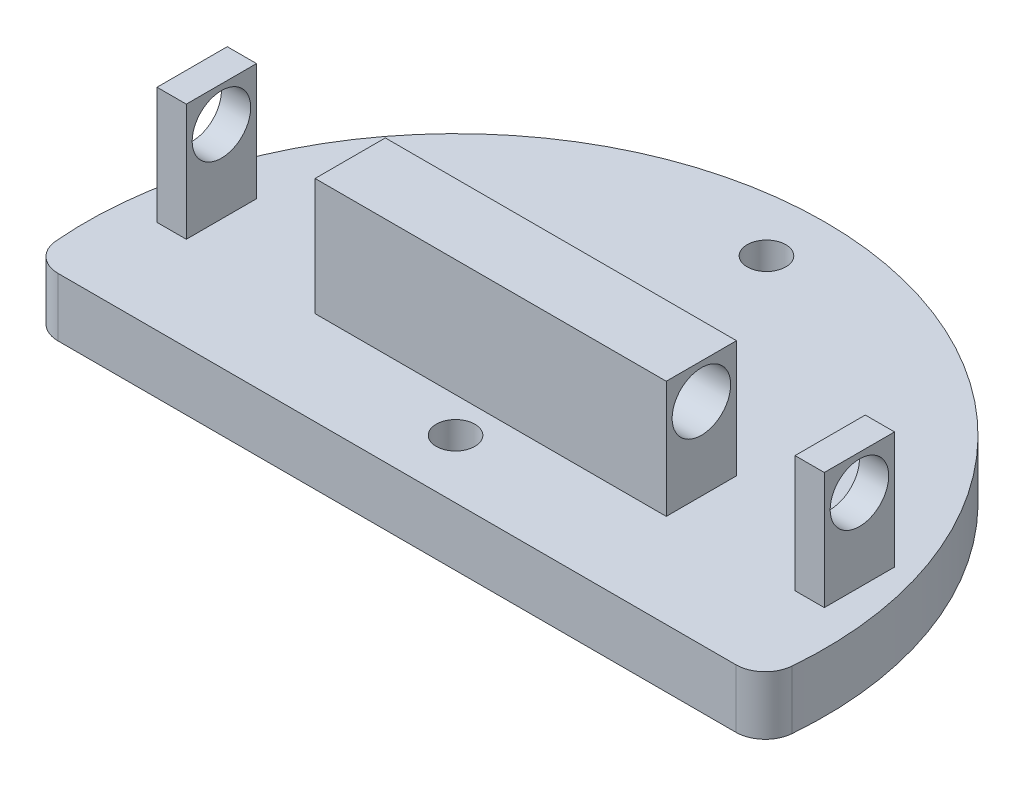
SolidWorks part; units mm, degrees
ref_plane "Front Plane" through (0, 0, 0) normal (0, 0, 1) x (1, 0, 0)
ref_plane "Top Plane" through (0, 0, 0) normal (0, 1, 0) x (1, 0, 0)
ref_plane "Right Plane" through (0, 0, 0) normal (1, 0, 0) x (0, 0, -1)
sketch "Sketch1" plane through (0, 0, 0) normal (0, 1, 0) x (1, 0, 0)
  line L0 (0, 0) -> (0, -5)
  line L1 (0, 26.56) -> (0, 31.56)
  line L2 (0, -5) -> (-31.1614, -5)
  line L3 (0, -5) -> (31.1614, -5)
  circle A0 centre (0, 0) radius 1.65
  circle A1 centre (0, 26.56) radius 1.65
  arc A3 (-31.1614, -5) -> (31.1614, -5) centre (0, 0) cw
  dimension "D1" = 3.3
  dimension "D2" = 3.3
  dimension "D3" = 26.56
  dimension "D5" = 5
  dimension "D4" = 5
extrude "Boss-Extrude1" add sketch "Sketch1" along normal blind 5
fillet "Fillet1" radius 2.5 2 edges at (-31.1614, 2.5, 5) (31.1614, 2.5, 5)
sketch "Sketch2" plane through (0, 5, 0) normal (0, 1, 0) x (1, 0, 0)
  line L0 (0, 0) -> (0, 3) construction
  line L2 (-28.5, 3) -> (-26, 3)
  line L3 (-28.5, 3) -> (-28.5, 9)
  line L4 (-28.5, 9) -> (-26, 9)
  line L5 (-26, 3) -> (-26, 9)
  line L6 (26, 3) -> (28.5, 3)
  line L7 (26, 3) -> (26, 9)
  line L8 (26, 9) -> (28.5, 9)
  line L9 (28.5, 3) -> (28.5, 9)
  line L10 (-15, 3) -> (15, 3)
  line L11 (-15, 3) -> (-15, 9)
  line L12 (-15, 9) -> (15, 9)
  line L13 (15, 3) -> (15, 9)
  dimension "D1" = 3
  dimension "D2" = 6
  dimension "D3" = 2.5
  dimension "D4" = 2.5
  dimension "D5" = 26
  dimension "D6" = 26
  dimension "D7" = 6
  dimension "D8" = 30
  dimension "D9" = 15
  dimension "D10" = 11
extrude "Boss-Extrude2" add sketch "Sketch2" along normal blind 10
sketch "Sketch3" plane through (-28.5, 0, 0) normal (-1, 0, 0) x (0, 0, 1)
  line L0 (-3, 15) -> (-3, 5) construction
  line L2 (-9, 15) -> (-3, 15) construction
  circle A0 centre (-6, 12) radius 2.5
  dimension "D1" = 5
  dimension "D2" = 3
  dimension "D3" = 3
extrude "Cut-Extrude1" cut sketch "Sketch3" against normal through all
